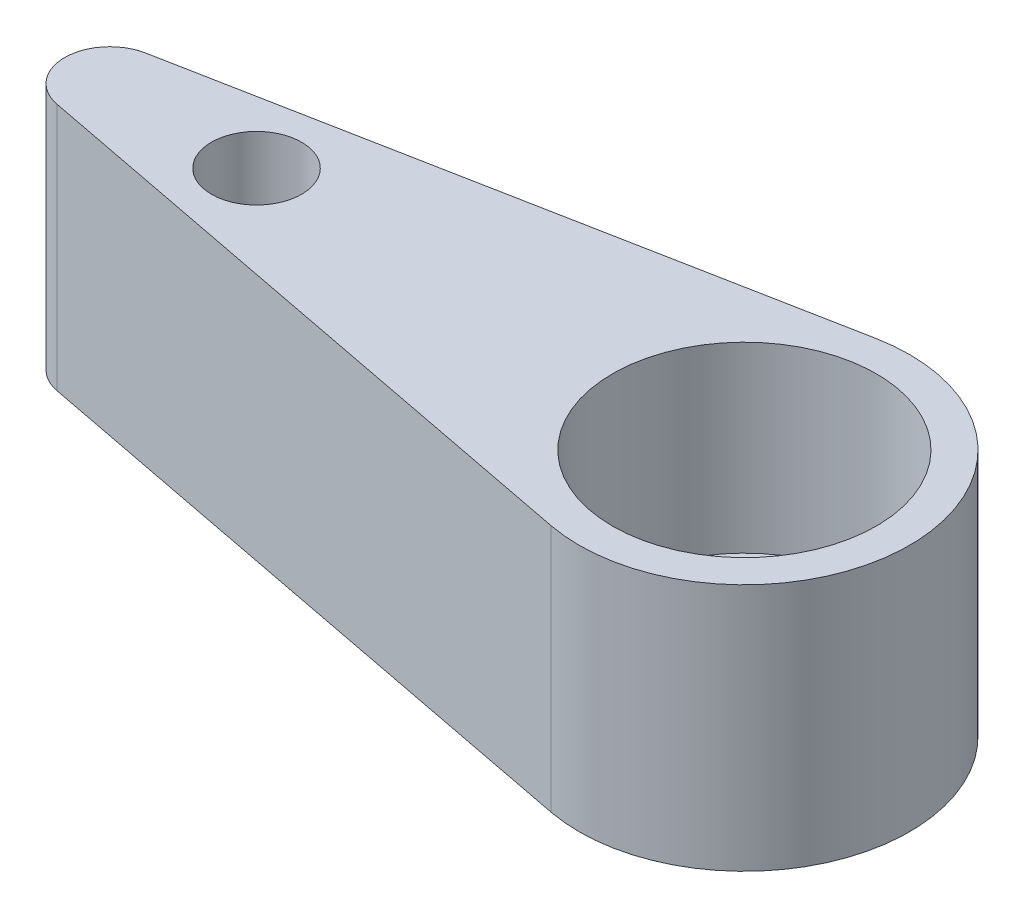
SolidWorks part; units mm, degrees
ref_plane "前视基准面" through (0, 0, 0) normal (0, 0, 1) x (1, 0, 0)
ref_plane "上视基准面" through (0, 0, 0) normal (0, 1, 0) x (1, 0, 0)
ref_plane "右视基准面" through (0, 0, 0) normal (1, 0, 0) x (0, 0, -1)
other "Configuration Table"
sketch "草图1" plane through (0, 0, 0) normal (0, 1, 0) x (1, 0, 0)
  line L0 (-0.6931, 3.596) -> (-14.2554, 0.9819)
  line L1 (-14.2554, -0.9819) -> (-0.6931, -3.596)
  line L2 (-0.6931, -3.596) -> (-0.6931, 3.596)
  line L3 (-3.6622, 0) -> (3.6622, 0) construction
  circle A0 centre (0, 0) radius 3.6622
  arc A1 (-14.2554, 0.9819) -> (-14.2554, -0.9819) centre (-14.0661, 0) ccw
  point P10 (-19.3497, 0)
  dimension "D1" = 19
  dimension "D3" = 1
  dimension "D2" = 19
extrude "凸台-拉伸4" add sketch "草图1" along normal blind 5.5 contours L2 L3 A0 | L3 L2 A0 | L0 A1 L1 A0 | A0 L3 L2 | L3 A0 L2
sketch "草图8" plane through (0, 5.5, 0) normal (0, 1, 0) x (1, 0, 0)
  line L0 (-3.6622, 0) -> (3.6622, 0) construction
  circle A0 centre (0, 0) radius 2.925
extrude "切除-拉伸8" cut sketch "草图8" against normal blind 4.05
sketch "草图9" plane through (0, 5.5, 0) normal (0, 1, 0) x (1, 0, 0)
  circle A0 centre (-10.8143, 0) radius 1
extrude "切除-拉伸9" cut sketch "草图9" against normal through all
sketch "草图10" plane through (0, 1.45, 0) normal (0, 1, 0) x (1, 0, 0)
  circle A0 centre (0, 0) radius 1
extrude "切除-拉伸10" cut sketch "草图10" against normal through all
